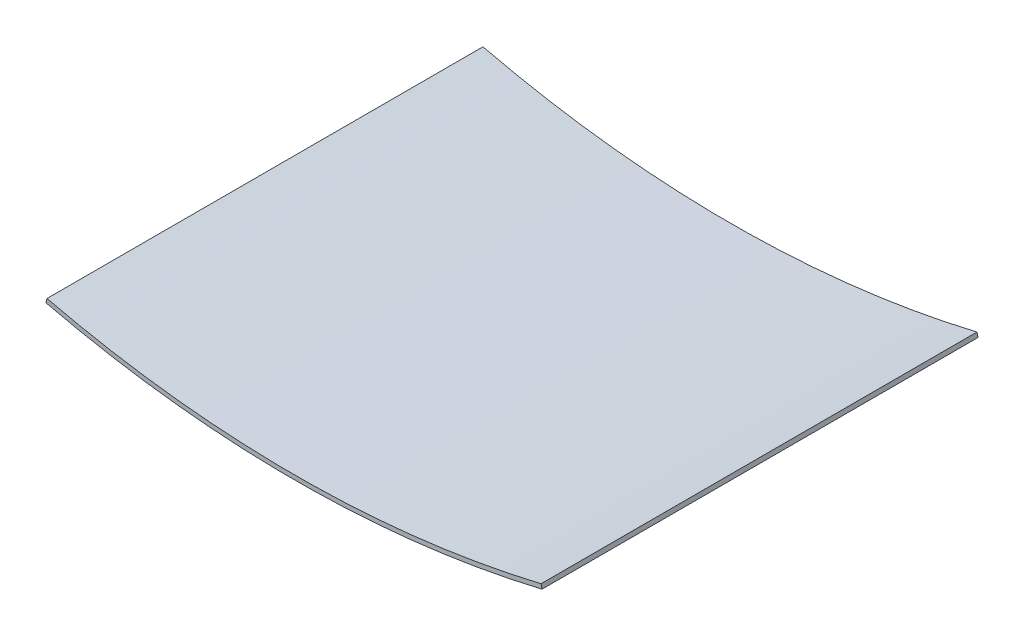
SolidWorks part; units mm, degrees
ref_plane "Front Plane" through (0, 0, 0) normal (0, 0, 1) x (1, 0, 0)
ref_plane "Top Plane" through (0, 0, 0) normal (0, 1, 0) x (1, 0, 0)
ref_plane "Right Plane" through (0, 0, 0) normal (1, 0, 0) x (0, 0, -1)
sketch "Sketch1" plane through (0, 0, 0) normal (0, 0, 1) x (1, 0, 0)
  line L0 (-215.9, 25.4) -> (215.9, 25.4) construction
  line L1 (0, 25.4) -> (0, 0) construction
  arc A0 (-215.9, 25.4) -> (215.9, 25.4) centre (0, 930.275) ccw
  dimension "D1" = 431.8
  dimension "D2" = 25.4
extrude "Extrude-Thin1" add sketch "Sketch1" along normal blind 381 thin
